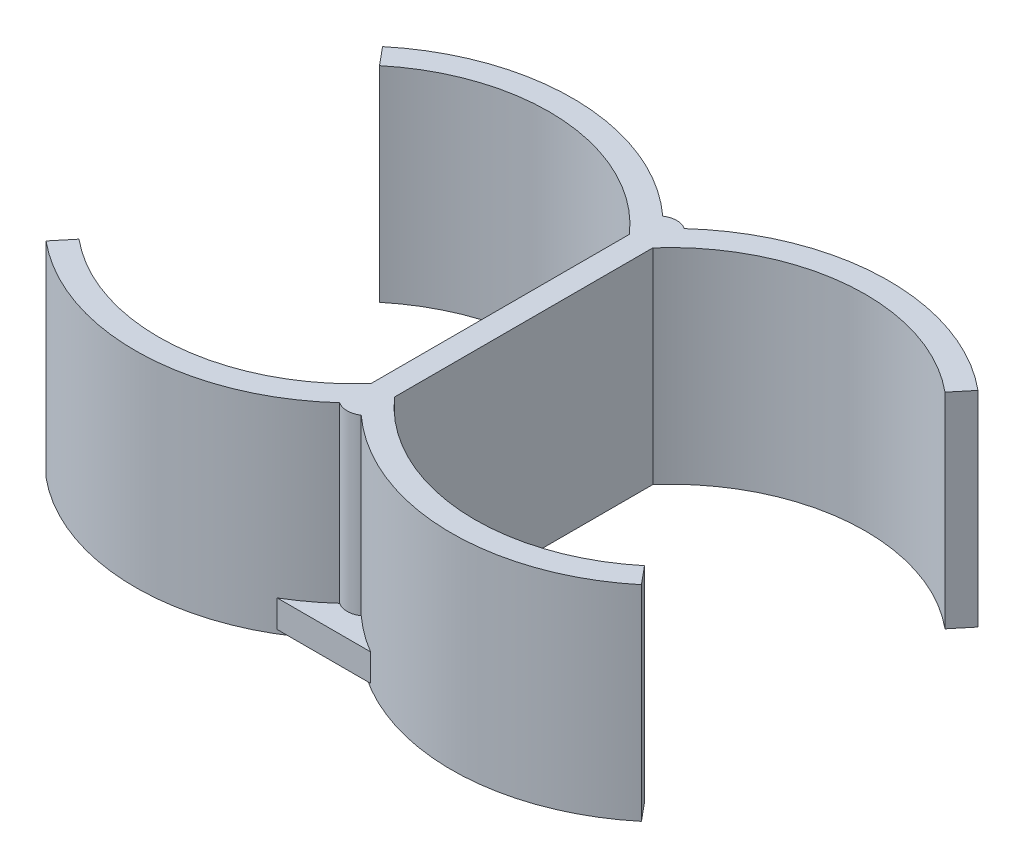
SolidWorks part; units mm, degrees
ref_plane "Front Plane" through (0, 0, 0) normal (0, 0, 1) x (1, 0, 0)
ref_plane "Top Plane" through (0, 0, 0) normal (0, 1, 0) x (1, 0, 0)
ref_plane "Right Plane" through (0, 0, 0) normal (1, 0, 0) x (0, 0, -1)
sketch "Sketch1" plane through (0, 0, 0) normal (0, 1, 0) x (1, 0, 0)
  line L0 (-18.0995, 0) -> (-19.2995, 0) construction
  line L1 (-0.6, -6.615) -> (0.6, -6.615)
  line L2 (-0.6, -6.615) -> (-0.6, 6.615)
  line L3 (-0.6, 6.615) -> (0.6, 6.615)
  line L4 (0.6, -6.615) -> (0.6, 6.615)
  line L5 (-0.6, -6.615) -> (0.6, 6.615) construction
  line L6 (-0.6, 6.615) -> (0.6, -6.615) construction
  line L7 (19.2995, 0) -> (18.0995, 0) construction
  line L8 (-15.25, 8.6203) -> (-14.4839, 7.6967)
  line L9 (15.25, 8.6203) -> (14.4839, 7.6967)
  line L10 (-15.25, -8.6203) -> (-14.4839, -7.6967)
  line L11 (15.25, -8.6203) -> (14.4839, -7.6967)
  circle A0 centre (8.0995, 0) radius 10
  circle A1 centre (8.0995, 0) radius 11.2
  circle A2 centre (-8.0995, 0) radius 10
  circle A3 centre (-8.0995, 0) radius 11.2
  point P0 (0, 0)
  dimension "D3" = 20
  dimension "D1" = 13.23
  dimension "D2" = 1.2
  dimension "D4" = 30.5
  dimension "D5" = 1.2
extrude "Boss-Extrude1" add sketch "Sketch1" along normal mid plane 10.5 contours L10 A3 A1 A2 | A3 A1 L11 A0 | A1 A3 A0 L1 A2 | A0 A2 L4 L2 | A0 A3 A1 A2 L3 | A1 A3 L8 A2 | A3 A0 L9 A1 | A2 L1 A0 | A2 A0 L4 | L2 A2 A0 | A2 A0 L3 | A0 A2 L2 | A2 L4 A0
sketch "Sketch3" plane through (0, -5.25, 0) normal (0, -1, 0) x (1, 0, 0)
  line L0 (0, -7.7356) -> (2.3902, -9.6356)
  line L1 (2.3902, -9.6356) -> (-2.3902, -9.6356)
  line L2 (-2.3902, -9.6356) -> (0, -7.7356)
  line L3 (0, 7.7356) -> (2.3902, 9.6356)
  line L4 (2.3902, 9.6356) -> (-2.3902, 9.6356)
  line L5 (-2.3902, 9.6356) -> (0, 7.7356)
  arc A0 (0, -7.7356) -> (15.25, -8.6203) centre (8.0995, 0) ccw construction
  arc A1 (-15.25, -8.6203) -> (0, -7.7356) centre (-8.0995, 0) ccw construction
  arc A2 (15.25, 8.6203) -> (0, 7.7356) centre (8.0995, 0) ccw construction
  arc A3 (0, 7.7356) -> (-15.25, 8.6203) centre (-8.0995, 0) ccw construction
  dimension "D1" = 1.9
extrude "Boss-Extrude2" add sketch "Sketch3" against normal blind 1.4 from offset 0.2 offset against normal yes
sketch "Sketch2" plane through (0, 5.25, 0) normal (0, 1, 0) x (1, 0, 0)
  circle A0 centre (0, 7.443) radius 1
  circle A1 centre (0, -7.443) radius 1
  arc A2 (-0.6, 6.615) -> (-14.4839, 7.6967) centre (-8.0995, 0) ccw construction
  arc A3 (0.6, -6.615) -> (14.4839, -7.6967) centre (8.0995, 0) ccw construction
  dimension "D1" = 2
extrude "Boss-Extrude3" add sketch "Sketch2" against normal up to surface (8.9 mm away) up to face at (0, -3.65, -9.0568)
